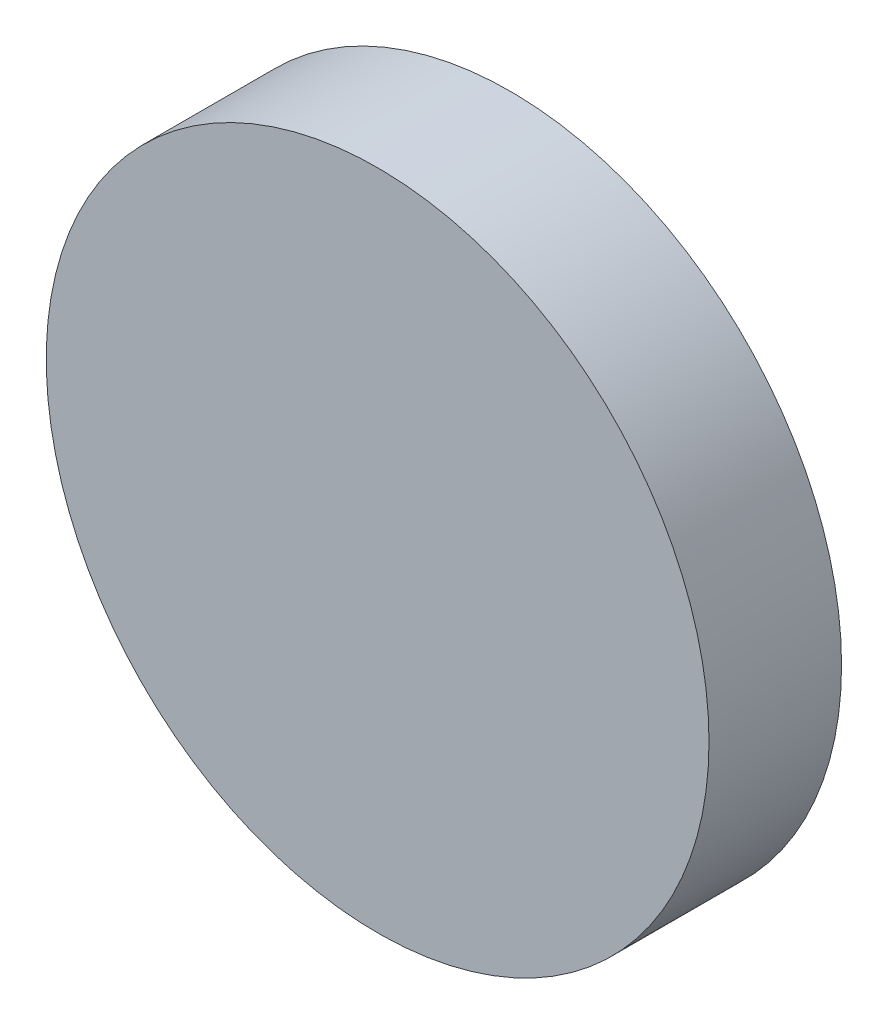
SolidWorks part; units mm, degrees
ref_plane "Front Plane" through (0, 0, 0) normal (0, 0, 1) x (1, 0, 0)
ref_plane "Top Plane" through (0, 0, 0) normal (0, 1, 0) x (1, 0, 0)
ref_plane "Right Plane" through (0, 0, 0) normal (1, 0, 0) x (0, 0, -1)
sketch "Sketch1" plane through (0, 0, 0) normal (0, 0, 1) x (1, 0, 0)
  circle A0 centre (2.5, 2.5) radius 2.5
  dimension "D1" = 5
extrude "Profile" add sketch "Sketch1" along normal blind 1
equation "\"Profile_Depth\" = 1mm"
equation "\"D1@Profile\" = \"Profile_Depth\""
equation "\"EnvelopeWidth\" = 5mm"
equation "\"EnvelopeHeight\" = 5mm"
